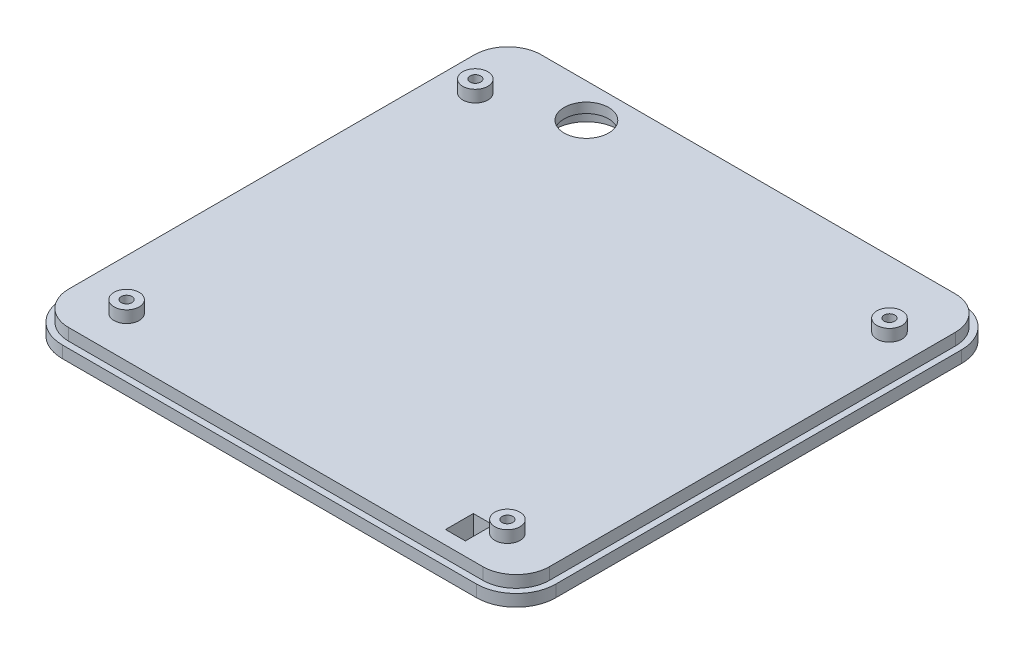
SolidWorks part; units mm, degrees
ref_plane "Front Plane" through (0, 0, 0) normal (0, 0, 1) x (1, 0, 0)
ref_plane "Top Plane" through (0, 0, 0) normal (0, 1, 0) x (1, 0, 0)
ref_plane "Right Plane" through (0, 0, 0) normal (1, 0, 0) x (0, 0, -1)
sketch "Sketch1" plane through (0, 0, 0) normal (0, 1, 0) x (1, 0, 0)
  line L0 (-52.2, 47.9825) -> (48, -44.1218) construction
  line L1 (-48, -44.1218) -> (52.2, 47.9825) construction
  line L2 (-52.2, 47.9825) -> (-48, -44.1218) construction
  line L3 (-48, -44.1218) -> (48, -44.1218) construction
  line L4 (48, -44.1218) -> (52.2, 47.9825) construction
  line L5 (52.2, 47.9825) -> (-52.2, 47.9825) construction
  line L7 (-52.2, 66.1825) -> (52.2, 66.1825)
  line L8 (-62.2, 56.1825) -> (-62.2, -46.1218)
  line L9 (-52.2, -56.1218) -> (52.2, -56.1218)
  line L10 (62.2, 56.1825) -> (62.2, -46.1218)
  circle A0 centre (-48, -44.1218) radius 1.35
  circle A1 centre (-52.2, 47.9825) radius 1.35
  circle A2 centre (52.2, 47.9825) radius 1.35
  circle A3 centre (48, -44.1218) radius 1.35
  arc A4 (-62.2, -46.1218) -> (-52.2, -56.1218) centre (-52.2, -46.1218) ccw
  arc A5 (52.2, -56.1218) -> (62.2, -46.1218) centre (52.2, -46.1218) ccw
  arc A6 (52.2, 66.1825) -> (62.2, 56.1825) centre (52.2, 56.1825) cw
  arc A7 (-52.2, 66.1825) -> (-62.2, 56.1825) centre (-52.2, 56.1825) ccw
  point P4 (0, 0)
  circle B0 centre (-52.2, 47.9825) radius 1.25 construction
  circle B1 centre (-48, -44.1218) radius 1.25 construction
  circle B2 centre (48, -44.1218) radius 1.25 construction
  circle B3 centre (52.2, 47.9825) radius 1.25 construction
  dimension "D8" = 2.7
  dimension "D9" = 10
  dimension "D10" = 10
  dimension "D11" = 10
  dimension "D12" = 10
  dimension "D1" = 104.4
  dimension "D2" = 96
  dimension "D3" = 12
  dimension "D4" = 10
  dimension "D5" = 18.2
  dimension "D6" = 10
  dimension "D7" = 92.1043
sketch_block_instance "Main Board-1"
sketch_block "Main Board" parameters "D1"=2.5, "D2"=104.4, "D3"=96, "D4"=92.2
extrude "Boss-Extrude1" add sketch "Sketch1" along normal blind 6 contours L7 A7 L8 A4 L9 A5 L10 A6 A0 A1 A2 A3
sketch "Sketch2" plane through (0, 0, 0) normal (0, -1, 0) x (1, 0, 0)
  line L4 (-52.2, -66.1825) -> (52.2, -66.1825)
  line L5 (62.2, -56.1825) -> (62.2, 46.1218)
  line L6 (52.2, 56.1218) -> (-52.2, 56.1218)
  line L7 (-62.2, 46.1218) -> (-62.2, -56.1825)
  line L8 (-52.2, -66.1825) -> (52.2, -66.1825)
  line L9 (62.2, -56.1825) -> (62.2, 46.1218)
  line L10 (52.2, 56.1218) -> (-52.2, 56.1218)
  line L11 (-62.2, 46.1218) -> (-62.2, -56.1825)
  circle A0 centre (-52.2, -47.9825) radius 1.35 construction
  circle A1 centre (52.2, -47.9825) radius 1.35 construction
  circle A2 centre (48, 44.1218) radius 1.35 construction
  circle A3 centre (-48, 44.1218) radius 1.35 construction
  arc A4 (52.2, -66.1825) -> (62.2, -56.1825) centre (52.2, -56.1825) ccw
  arc A5 (62.2, 46.1218) -> (52.2, 56.1218) centre (52.2, 46.1218) ccw
  arc A6 (-52.2, 56.1218) -> (-62.2, 46.1218) centre (-52.2, 46.1218) ccw
  arc A7 (-62.2, -56.1825) -> (-52.2, -66.1825) centre (-52.2, -56.1825) ccw
  arc A8 (52.2, -66.1825) -> (62.2, -56.1825) centre (52.2, -56.1825) ccw
  arc A9 (62.2, 46.1218) -> (52.2, 56.1218) centre (52.2, 46.1218) ccw
  arc A10 (-52.2, 56.1218) -> (-62.2, 46.1218) centre (-52.2, 46.1218) ccw
  arc A11 (-62.2, -56.1825) -> (-52.2, -66.1825) centre (-52.2, -56.1825) ccw
  circle A12 centre (-52.2, -47.9825) radius 1.35
  circle A13 centre (52.2, -47.9825) radius 1.35
  circle A14 centre (48, 44.1218) radius 1.35
  circle A15 centre (-48, 44.1218) radius 1.35
  circle A16 centre (-48, 44.1218) radius 2.5
  circle A17 centre (48, 44.1218) radius 2.5
  circle A18 centre (52.2, -47.9825) radius 2.5
  circle A19 centre (-52.2, -47.9825) radius 2.5
  circle M9 centre (-48, 44.1218) radius 1.35
  circle M10 centre (-52.2, -47.9825) radius 1.35
  circle M11 centre (52.2, -47.9825) radius 1.35
  circle M12 centre (48, 44.1218) radius 1.35
  dimension "D2" = 5
  dimension "D1" = 0
extrude "Cut-Extrude1" cut sketch "Sketch2" against normal blind 3 contours A16 M9 | A19 M10 | A18 M11 | A17 M12
sketch "Sketch3" plane through (0, 6, 0) normal (0, 1, 0) x (1, 0, 0)
  circle A0 centre (-48, -44.1218) radius 1.35 construction
  circle A1 centre (48, -44.1218) radius 1.35 construction
  circle A2 centre (52.2, 47.9825) radius 1.35 construction
  circle A3 centre (-52.2, 47.9825) radius 1.35 construction
  circle A4 centre (-48, -44.1218) radius 1.35
  circle A5 centre (48, -44.1218) radius 1.35
  circle A6 centre (52.2, 47.9825) radius 1.35
  circle A7 centre (-52.2, 47.9825) radius 1.35
  circle A8 centre (-52.2, 47.9825) radius 3.175
  circle A9 centre (52.2, 47.9825) radius 3.175
  circle A10 centre (48, -44.1218) radius 3.175
  circle A11 centre (-48, -44.1218) radius 3.175
  circle M1 centre (-48, -44.1218) radius 1.35
  circle M2 centre (-52.2, 47.9825) radius 1.35
  circle M3 centre (52.2, 47.9825) radius 1.35
  circle M4 centre (48, -44.1218) radius 1.35
  dimension "D1" = 6.35
extrude "Boss-Extrude2" add sketch "Sketch3" along normal blind 3 contours A8 M2 | A9 M3 | A10 M4 | A11 M1 | A7 | A5
sketch "Sketch4" plane through (0, 6, 0) normal (0, 1, 0) x (1, 0, 0)
  line L0 (-60.6, 56.1825) -> (-60.6, -46.1218)
  line L1 (-52.2, -54.5218) -> (52.2, -54.5218)
  line L2 (60.6, -46.1218) -> (60.6, 56.1825)
  line L3 (52.2, 64.5825) -> (-52.2, 64.5825)
  line L4 (52.2, 66.1825) -> (-52.2, 66.1825)
  line L5 (-62.2, 56.1825) -> (-62.2, -46.1218)
  line L6 (-52.2, -56.1218) -> (52.2, -56.1218)
  line L7 (62.2, -46.1218) -> (62.2, 56.1825)
  line L8 (52.2, 66.1825) -> (-52.2, 66.1825)
  line L9 (-62.2, 56.1825) -> (-62.2, -46.1218)
  line L10 (-52.2, -56.1218) -> (52.2, -56.1218)
  line L11 (62.2, -46.1218) -> (62.2, 56.1825)
  arc A0 (-52.2, 64.5825) -> (-60.6, 56.1825) centre (-52.2, 56.1825) ccw
  arc A1 (-60.6, -46.1218) -> (-52.2, -54.5218) centre (-52.2, -46.1218) ccw
  arc A2 (52.2, -54.5218) -> (60.6, -46.1218) centre (52.2, -46.1218) ccw
  arc A3 (60.6, 56.1825) -> (52.2, 64.5825) centre (52.2, 56.1825) ccw
  arc A4 (-52.2, 66.1825) -> (-62.2, 56.1825) centre (-52.2, 56.1825) ccw
  arc A5 (-62.2, -46.1218) -> (-52.2, -56.1218) centre (-52.2, -46.1218) ccw
  arc A6 (52.2, -56.1218) -> (62.2, -46.1218) centre (52.2, -46.1218) ccw
  arc A7 (62.2, 56.1825) -> (52.2, 66.1825) centre (52.2, 56.1825) ccw
  arc A8 (-52.2, 66.1825) -> (-62.2, 56.1825) centre (-52.2, 56.1825) ccw
  arc A9 (-62.2, -46.1218) -> (-52.2, -56.1218) centre (-52.2, -46.1218) ccw
  arc A10 (52.2, -56.1218) -> (62.2, -46.1218) centre (52.2, -46.1218) ccw
  arc A11 (62.2, 56.1825) -> (52.2, 66.1825) centre (52.2, 56.1825) ccw
  dimension "D1" = 0
  dimension "D2" = 1.6
extrude "Cut-Extrude2" cut sketch "Sketch4" against normal blind 3
sketch "Sketch5" plane through (0, 6, 0) normal (0, 1, 0) x (1, 0, 0)
  circle A0 centre (-35.1, 52.7125) radius 1.35
  circle A1 centre (50.09, 37.7525) radius 1.35
  dimension "D1" = 4.73
  dimension "D3" = 2.7
  dimension "D2" = 17.1
  dimension "D4" = 10.23
  dimension "D5" = 2.11
sketch "Sketch7" plane through (0, 6, 0) normal (0, 1, 0) x (1, 0, 0)
  circle A0 centre (-32.2, 55.9825) radius 5.6
  dimension "D1" = 11.2
  dimension "D2" = 8
  dimension "D3" = 20
extrude "Cut-Extrude3" cut sketch "Sketch7" against normal blind 10
sketch "Sketch8" plane through (0, 0, 0) normal (0, -1, 0) x (1, 0, 0)
  circle A0 centre (-32.2, -55.9825) radius 5.6 construction
  circle A1 centre (-32.2, -55.9825) radius 5.6
  circle A2 centre (-32.2, -55.9825) radius 8
  dimension "D1" = 16
extrude "Cut-Extrude4" cut sketch "Sketch8" against normal blind 3.5
sketch "Sketch9" plane through (0, 0, 0) normal (0, -1, 0) x (1, 0, 0)
  line L1 (44.4, 44.1218) -> (39.4, 44.1218)
  line L2 (44.4, 44.1218) -> (44.4, 51.1218)
  line L3 (44.4, 51.1218) -> (39.4, 51.1218)
  line L4 (39.4, 44.1218) -> (39.4, 51.1218)
  point P4 (41.9, 51.1218)
  point P5 (44.4, 47.6218)
  dimension "D1" = 7
  dimension "D2" = 5
  dimension "D3" = 6.1
  dimension "D4" = 3.5
extrude "Cut-Extrude5" cut sketch "Sketch9" against normal through all
